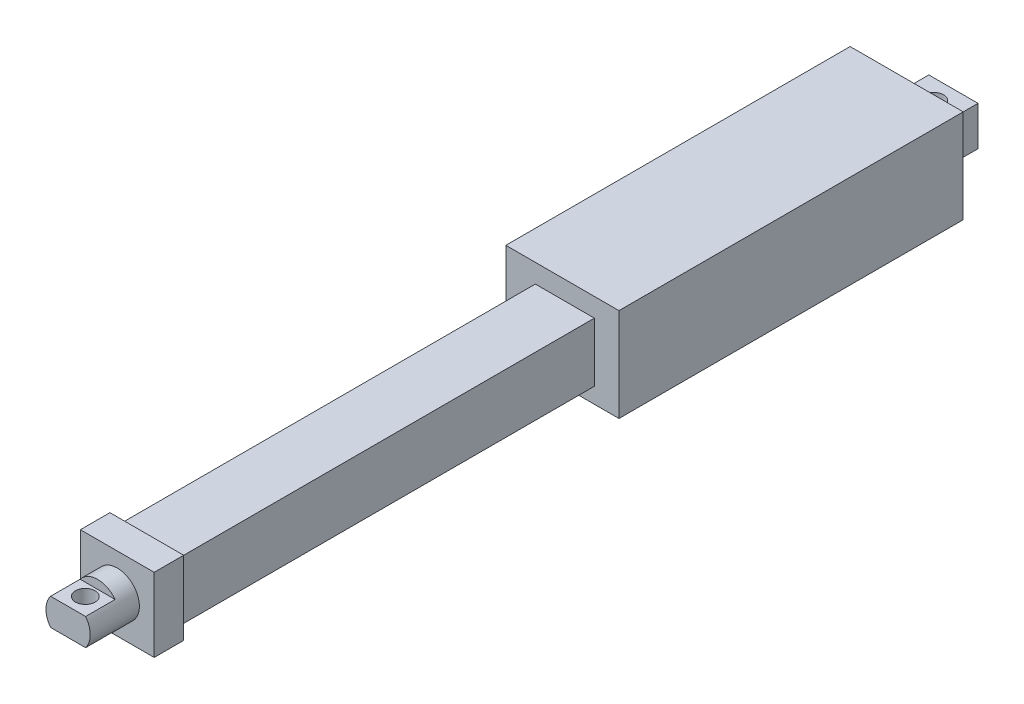
SolidWorks part; units mm, degrees
ref_plane "Front Plane" through (0, 0, 0) normal (0, 0, 1) x (1, 0, 0)
ref_plane "Top Plane" through (0, 0, 0) normal (0, 1, 0) x (1, 0, 0)
ref_plane "Right Plane" through (0, 0, 0) normal (1, 0, 0) x (0, 0, -1)
sketch "Sketch2" plane through (0, 0, 0) normal (0, 0, 1) x (1, 0, 0)
  line L1 (-11.7315, 10.9732) -> (11.2685, 10.9732)
  line L2 (-11.7315, 10.9732) -> (-11.7315, -8.0268)
  line L3 (-11.7315, -8.0268) -> (11.2685, -8.0268)
  line L4 (11.2685, 10.9732) -> (11.2685, -8.0268)
  dimension "D1" = 23
  dimension "D2" = 19
extrude "Boss-Extrude1" add sketch "Sketch2" along normal blind 70
sketch "Sketch3" plane through (0, 0, 0) normal (0, 0, -1) x (-1, 0, 0)
  line L0 (11.7315, -8.0268) -> (-11.2685, -8.0268) construction
  line L1 (-5.2685, 4.9732) -> (4.7315, 4.9732)
  line L2 (-5.2685, 4.9732) -> (-5.2685, -3.0268)
  line L3 (-5.2685, -3.0268) -> (4.7315, -3.0268)
  line L4 (4.7315, 4.9732) -> (4.7315, -3.0268)
  line L5 (-11.2685, -8.0268) -> (-11.2685, 10.9732) construction
  dimension "D1" = 10
  dimension "D2" = 8
  dimension "D3" = 5
  dimension "D4" = 6
extrude "Boss-Extrude2" add sketch "Sketch3" along normal blind 9
sketch "Sketch4" plane through (0, 4.9732, 0) normal (0, 1, 0) x (1, 0, 0)
  line L0 (-4.7315, 9) -> (5.2685, 9) construction
  line L1 (5.2685, 9) -> (5.2685, 0) construction
  circle A0 centre (0.2685, 5) radius 2
  dimension "D1" = 4
  dimension "D2" = 5
extrude "Cut-Extrude1" cut sketch "Sketch4" against normal through all
sketch "Sketch5" plane through (0, 0, 70) normal (0, 0, 1) x (1, 0, 0)
  line L0 (-11.7315, -8.0268) -> (11.2685, -8.0268) construction
  line L1 (6.2685, -4.8518) -> (-5.7315, -4.8518)
  line L2 (6.2685, -4.8518) -> (6.2685, 7.1482)
  line L3 (6.2685, 7.1482) -> (-5.7315, 7.1482)
  line L4 (-5.7315, -4.8518) -> (-5.7315, 7.1482)
  line L5 (11.2685, -8.0268) -> (11.2685, 10.9732) construction
  dimension "D1" = 12
  dimension "D2" = 12
  dimension "D3" = 3.175
  dimension "D4" = 5
extrude "Boss-Extrude3" add sketch "Sketch5" along normal blind 85
sketch "Sketch6" plane through (0, 0, 155) normal (0, 0, 1) x (1, 0, 0)
  line L0 (-5.7315, -4.8518) -> (6.2685, -4.8518) construction
  line L1 (7.7685, -6.3518) -> (-7.2315, -6.3518)
  line L2 (7.7685, -6.3518) -> (7.7685, 8.6482)
  line L3 (7.7685, 8.6482) -> (-7.2315, 8.6482)
  line L4 (-7.2315, -6.3518) -> (-7.2315, 8.6482)
  line L5 (-5.7315, 7.1482) -> (-5.7315, -4.8518) construction
  dimension "D1" = 15
  dimension "D2" = 15
  dimension "D3" = 1.5
  dimension "D4" = 1.5
extrude "Boss-Extrude4" add sketch "Sketch6" along normal blind 6
sketch "Sketch7" plane through (0, 0, 161) normal (0, 0, 1) x (1, 0, 0)
  line L0 (0.2685, -6.3518) -> (0.2685, 8.6482)
  line L1 (-7.2315, -6.3518) -> (7.7685, -6.3518) construction
  line L2 (7.7685, 8.6482) -> (-7.2315, 8.6482) construction
  line L3 (7.7685, 1.1482) -> (-7.2315, 1.1482)
  line L4 (7.7685, -6.3518) -> (7.7685, 8.6482) construction
  line L5 (-7.2315, 8.6482) -> (-7.2315, -6.3518) construction
  circle A0 centre (0.2685, 1.1482) radius 4.5
extrude "Boss-Extrude5" add sketch "Sketch7" along normal blind 10 contours L0 A0 L3 | L3 A0 L0 | L3 A0 L0 | L0 A0 L3
sketch "Sketch8" plane through (0, 0, 171) normal (0, 0, 1) x (1, 0, 0)
  line L0 (0.2685, -3.3518) -> (0.2685, 5.6482)
  line L1 (4.7685, 1.1482) -> (-4.2315, 1.1482)
  line L3 (4.7685, 1.1482) -> (-4.2315, 1.1482)
  line L4 (4.7685, 1.1482) -> (4.7685, -1.6018)
  line L5 (4.7685, -1.6018) -> (-4.2315, -1.6018)
  line L6 (-4.2315, 1.1482) -> (-4.2315, -1.6018)
  line L7 (4.7685, 1.1482) -> (-4.2315, 1.1482)
  line L8 (4.7685, 1.1482) -> (4.7685, 3.8982)
  line L9 (4.7685, 3.8982) -> (-4.2315, 3.8982)
  line L10 (-4.2315, 1.1482) -> (-4.2315, 3.8982)
  circle A0 centre (0.2685, 1.1482) radius 4.5 construction
  circle M3 centre (0.2685, 1.1482) radius 4.5
  dimension "D1" = 2.75
  dimension "D2" = 2.75
extrude "Cut-Extrude2" cut sketch "Sketch8" against normal blind 6 contours L9 L0 M3 | L9 L0 M3 | L0 L5 M3 | L5 L0 M3
sketch "Sketch9" plane through (0, 3.8982, 0) normal (0, 1, 0) x (1, 0, 0)
  line L0 (-3.2935, -165) -> (-3.2935, -171) construction
  line L1 (3.8304, -171) -> (-3.2935, -171) construction
  circle A0 centre (0.2665, -167.5) radius 2
  dimension "D1" = 3.56
  dimension "D2" = 3.5
extrude "Cut-Extrude3" cut sketch "Sketch9" against normal through all
